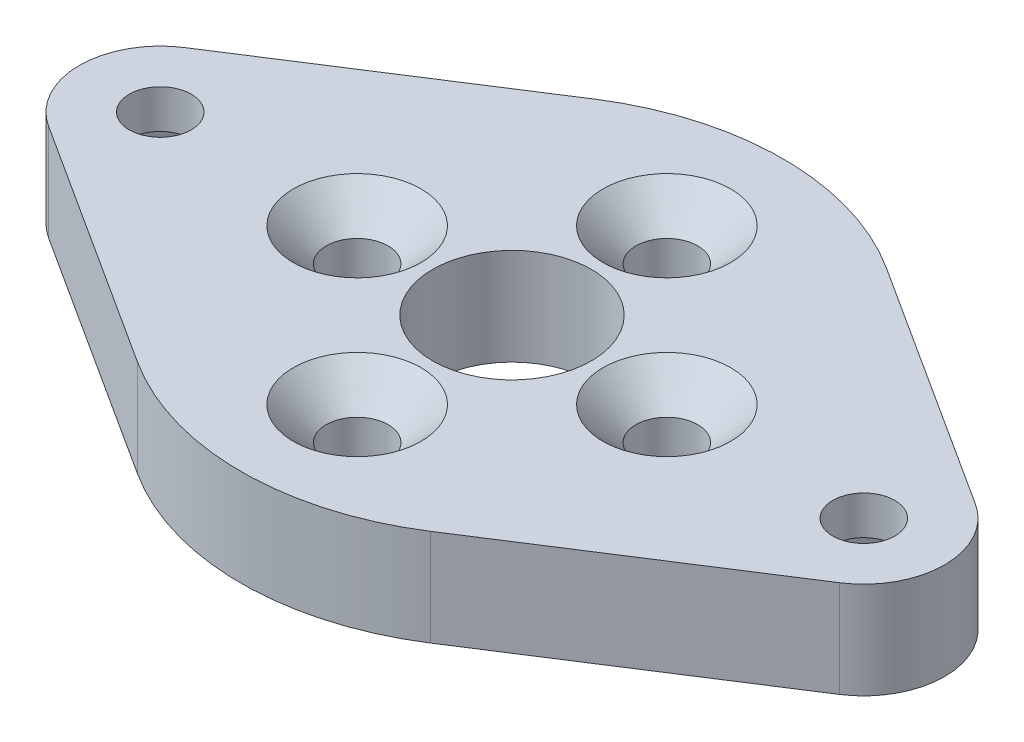
SolidWorks part; units mm, degrees
material "ABS"
ref_plane "Front Plane" through (0, 0, 0) normal (0, 0, 1) x (1, 0, 0)
ref_plane "Top Plane" through (0, 0, 0) normal (0, 1, 0) x (1, 0, 0)
ref_plane "Right Plane" through (0, 0, 0) normal (1, 0, 0) x (0, 0, -1)
sketch "Sketch1" plane through (0, 0, 0) normal (0, 1, 0) x (1, 0, 0)
  line L0 (18.1754, 0) -> (-18.1754, 0) construction
  line L2 (-20.4324, 3.5129) -> (-7.5676, 11.7784)
  line L3 (-21.3509, 0) -> (-19.7631, -2.75) construction
  line L4 (-19.7631, -2.75) -> (-16.5877, -2.75) construction
  line L5 (-16.5877, -2.75) -> (-15, 0) construction
  line L6 (-15, 0) -> (-16.5877, 2.75) construction
  line L7 (-16.5877, 2.75) -> (-19.7631, 2.75) construction
  line L8 (-19.7631, 2.75) -> (-21.3509, 0) construction
  line L9 (-20.4324, -3.5129) -> (-7.5676, -11.7784)
  line L10 (0, 0) -> (0, 14) construction
  line L11 (20.4324, -3.5129) -> (7.5676, -11.7784)
  line L12 (20.4324, 3.5129) -> (7.5676, 11.7784)
  circle A0 centre (0, 0) radius 8 construction
  circle A1 centre (0, 0) radius 4.1
  arc A6 (-7.5676, -11.7784) -> (7.5676, -11.7784) centre (0, 0) ccw
  circle A7 centre (-18.1754, 0) radius 1.6
  circle A8 centre (18.1754, 0) radius 1.6
  circle A9 centre (-18.1754, 0) radius 2.75 construction
  arc A10 (-20.4324, 3.5129) -> (-20.4324, -3.5129) centre (-18.1754, 0) ccw
  arc A11 (20.4324, 3.5129) -> (20.4324, -3.5129) centre (18.1754, 0) cw
  arc A12 (7.5676, 11.7784) -> (-7.5676, 11.7784) centre (0, 0) ccw
  circle A13 centre (0, 8) radius 1.6
  circle A14 centre (8, 0) radius 1.6
  circle A15 centre (0, -8) radius 1.6
  circle A16 centre (-8, 0) radius 1.6
  point P9 (0, 0)
  point P16 (0, 0)
  dimension "D1" = 16
  dimension "D2" = 8.2
  dimension "D4" = 3.2
  dimension "D6" = 28
  dimension "D7" = 3.2
  dimension "D9" = 15
  dimension "D8" = 5.5
extrude "Boss-Extrude1" add sketch "Sketch1" along normal blind 5
chamfer "Chamfer1" distance 1.7 angle 45 4 edges at (-8, 5, 1.6) (0, 5, -6.4) (8, 5, 1.6) (0, 5, 9.6)
sketch "Sketch2" plane through (0, 0, 0) normal (0, -1, 0) x (1, 0, 0)
  line L1 (-15, 0) -> (-16.5877, 2.75)
  line L2 (-16.5877, 2.75) -> (-19.7631, 2.75)
  line L3 (-19.7631, 2.75) -> (-21.3509, 0)
  line L4 (-21.3509, 0) -> (-19.7631, -2.75)
  line L5 (-19.7631, -2.75) -> (-16.5877, -2.75)
  line L6 (-16.5877, -2.75) -> (-15, 0)
  line L7 (15, 0) -> (16.5877, -2.75)
  line L8 (16.5877, -2.75) -> (19.7631, -2.75)
  line L9 (19.7631, -2.75) -> (21.3509, 0)
  line L10 (21.3509, 0) -> (19.7631, 2.75)
  line L11 (19.7631, 2.75) -> (16.5877, 2.75)
  line L12 (16.5877, 2.75) -> (15, 0)
  circle A0 centre (-18.1754, 0) radius 2.75 construction
  circle A1 centre (18.1754, 0) radius 2.75 construction
  dimension "D1" = 5.5
extrude "Cut-Extrude1" cut sketch "Sketch2" against normal blind 3
